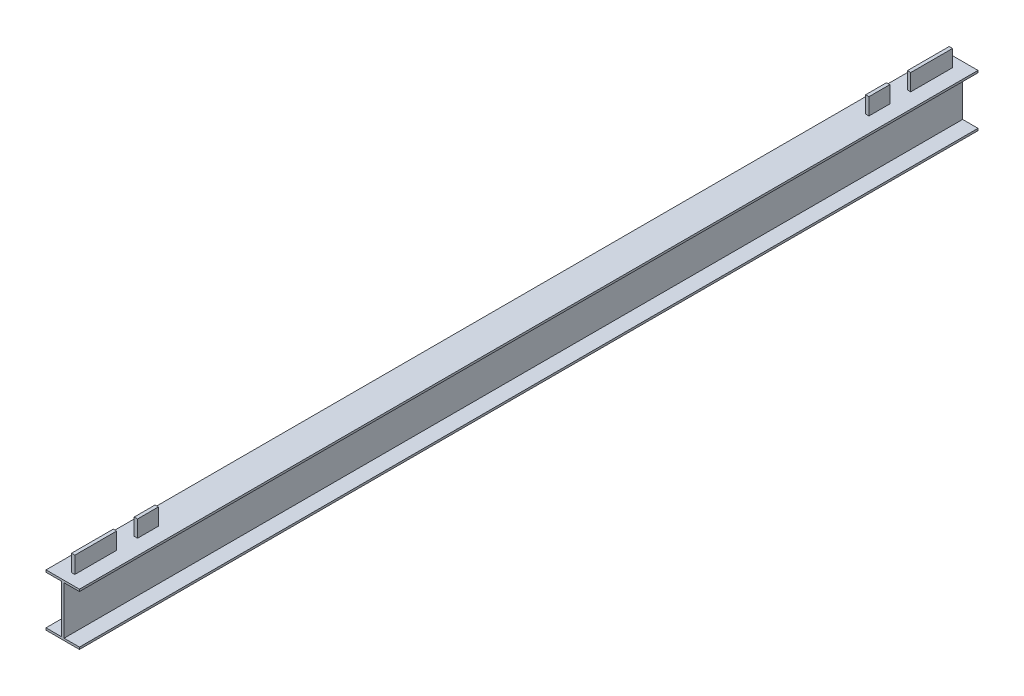
SolidWorks part; units mm, degrees
ref_plane "前视基准面" through (0, 0, 0) normal (0, 0, 1) x (1, 0, 0)
ref_plane "上视基准面" through (0, 0, 0) normal (0, 1, 0) x (1, 0, 0)
ref_plane "右视基准面" through (0, 0, 0) normal (1, 0, 0) x (0, 0, -1)
sketch "草图2" plane through (0, 0, 0) normal (0, 0, 1) x (1, 0, 0)
  line L1 (0, 0) -> (160, 0)
  line L2 (0, 0) -> (0, 250)
  line L3 (0, 250) -> (160, 250)
  line L4 (160, 0) -> (160, 250)
  dimension "D1" = 160
  dimension "D2" = 250
extrude "凸台-拉伸1" add sketch "草图2" along normal blind 4300
sketch "草图3" plane through (0, 0, 4300) normal (0, 0, 1) x (1, 0, 0)
  line L0 (80, -750) -> (80, 49250) construction
  line L1 (160, 250) -> (0, 250) construction
  line L2 (160, 0) -> (160, 250) construction
  line L3 (160, 240) -> (86.5, 240)
  line L4 (160, 240) -> (160, 10)
  line L5 (160, 10) -> (86.5, 10)
  line L6 (86.5, 240) -> (86.5, 10)
  line L7 (0, 250) -> (0, 0) construction
  line L8 (0, 240) -> (73.5, 240)
  line L9 (0, 240) -> (0, 10)
  line L10 (0, 10) -> (73.5, 10)
  line L11 (73.5, 240) -> (73.5, 10)
  line L12 (-840, 125) -> (49160, 125) construction
  point P5 (80, 250)
  point P20 (160, 125)
  dimension "D1" = 10
  dimension "D2" = 13
extrude "切除-拉伸1" cut sketch "草图3" against normal through all
sketch "草图4" plane through (0, 250, 0) normal (0, 1, 0) x (1, 0, 0)
  line L0 (80, -1000) -> (80, 49000) construction
  line L1 (160, 0) -> (0, 0) construction
  line L2 (160, -4300) -> (0, -4300) construction
  line L3 (72, -50) -> (88, -50)
  line L4 (72, -50) -> (72, -250)
  line L5 (72, -250) -> (88, -250)
  line L6 (88, -50) -> (88, -250)
  line L7 (72, -350) -> (88, -350)
  line L8 (72, -350) -> (72, -450)
  line L9 (72, -450) -> (88, -450)
  line L10 (88, -350) -> (88, -450)
  line L11 (72, -4050) -> (88, -4050)
  line L12 (72, -4050) -> (72, -4250)
  line L13 (72, -4250) -> (88, -4250)
  line L14 (88, -4050) -> (88, -4250)
  line L15 (72, -3850) -> (88, -3850)
  line L16 (72, -3850) -> (72, -3950)
  line L17 (72, -3950) -> (88, -3950)
  line L18 (88, -3850) -> (88, -3950)
  point P5 (80, 0)
  dimension "D1" = 16
  dimension "D2" = 50
  dimension "D3" = 100
  dimension "D4" = 100
  dimension "D5" = 200
  dimension "D6" = 100
  dimension "D7" = 100
  dimension "D8" = 50
  dimension "D9" = 200
extrude "凸台-拉伸2" add sketch "草图4" along normal blind 80
